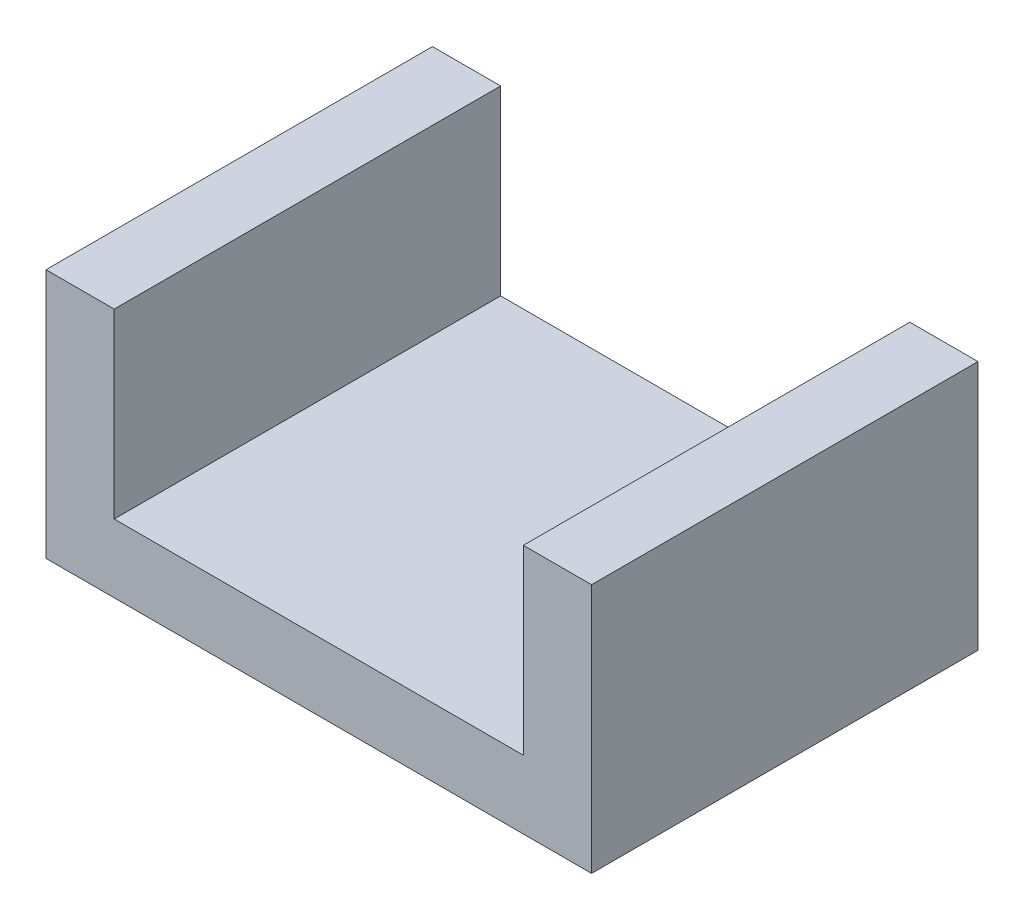
SolidWorks part; units mm, degrees
ref_plane "Plano frontal" through (0, 0, 0) normal (0, 0, 1) x (1, 0, 0)
ref_plane "Plano superior" through (0, 0, 0) normal (0, 1, 0) x (1, 0, 0)
ref_plane "Plano direito" through (0, 0, 0) normal (1, 0, 0) x (0, 0, -1)
sketch "Esboço1" plane through (0, 0, 0) normal (0, 0, 1) x (1, 0, 0)
  line L0 (-9.9954, 0) -> (-9.9954, 7.9981)
  line L1 (8.0046, 0) -> (8.0046, 7.9981)
  line L2 (-9.9954, 0) -> (8.0046, 0)
  line L3 (8.0046, 7.9981) -> (11.0046, 7.9981)
  line L4 (11.0046, 7.9981) -> (11.0046, -3.0019)
  line L5 (-9.9954, 7.9981) -> (-12.9954, 7.9981)
  line L6 (-12.9954, 7.9981) -> (-12.9954, -3.0019)
  line L7 (-12.9954, -3.0019) -> (11.0046, -3.0019)
  dimension "D1" = 11
  dimension "D2" = 3
  dimension "D3" = 3
  dimension "D4" = 18
  dimension "D5" = 11
extrude "Ressalto-extrusão1" add sketch "Esboço1" against normal blind 17
